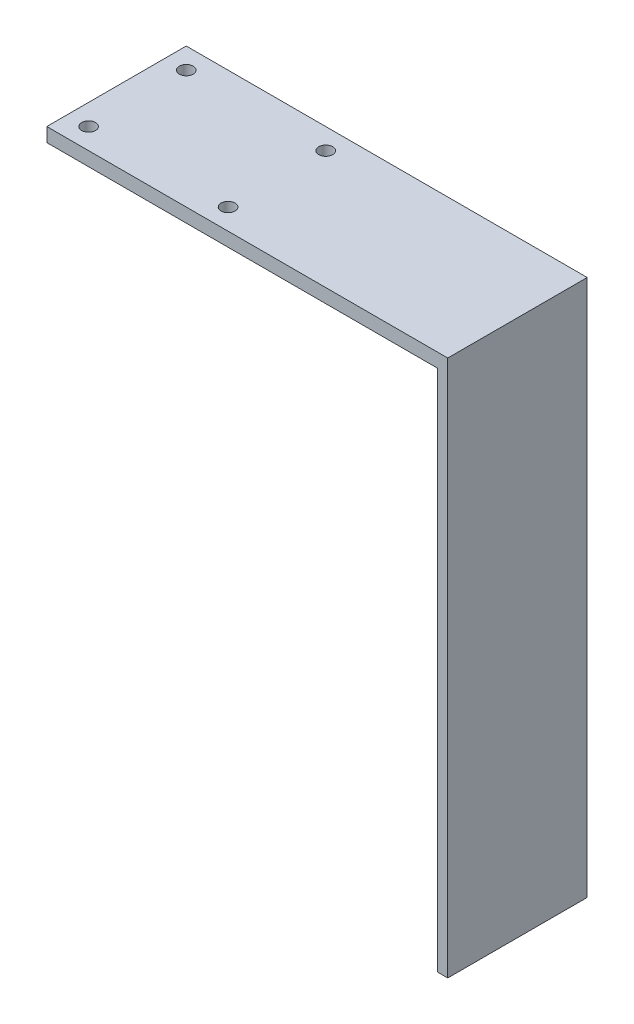
SolidWorks part; units mm, degrees
ref_plane "Front Plane" through (0, 0, 0) normal (0, 0, 1) x (1, 0, 0)
ref_plane "Top Plane" through (0, 0, 0) normal (0, 1, 0) x (1, 0, 0)
ref_plane "Right Plane" through (0, 0, 0) normal (1, 0, 0) x (0, 0, -1)
sketch "Sketch1" plane through (0, 0, 0) normal (0, 1, 0) x (1, 0, 0)
  line L1 (-57.5, 20) -> (57.5, 20)
  line L2 (-57.5, 20) -> (-57.5, -20)
  line L3 (-57.5, -20) -> (57.5, -20)
  line L4 (57.5, 20) -> (57.5, -20)
  line L5 (-57.5, 20) -> (57.5, -20) construction
  line L6 (-57.5, -20) -> (57.5, 20) construction
  line L7 (-51.5, 14) -> (-11.5, 14) construction
  line L8 (-51.5, 14) -> (-51.5, -14) construction
  line L9 (-51.5, -14) -> (-11.5, -14) construction
  line L10 (-11.5, 14) -> (-11.5, -14) construction
  circle A0 centre (-11.5, 14) radius 2
  circle A1 centre (-11.5, -14) radius 2
  circle A2 centre (-51.5, -14) radius 2
  circle A3 centre (-51.5, 14) radius 2
  point P0 (0, 0)
  point P6 (0, 0)
  dimension "D5" = 4
  dimension "D6" = 4
  dimension "D7" = 4
  dimension "D8" = 4
  dimension "D1" = 40
  dimension "D2" = 115
  dimension "D3" = 40
  dimension "D4" = 28
  dimension "D9" = 6
  dimension "D10" = 6
extrude "Boss-Extrude1" add sketch "Sketch1" along normal blind 4
sketch "Sketch3" plane through (0, 0, 0) normal (0, -1, 0) x (1, 0, 0)
  line L0 (57.5, -20) -> (-57.5, -20) construction
  line L1 (57.5, 20) -> (54.5, 20)
  line L2 (57.5, 20) -> (57.5, -20)
  line L3 (57.5, -20) -> (54.5, -20)
  line L4 (54.5, 20) -> (54.5, -20)
  dimension "D1" = 3
extrude "Boss-Extrude3" add sketch "Sketch3" along normal blind 150
